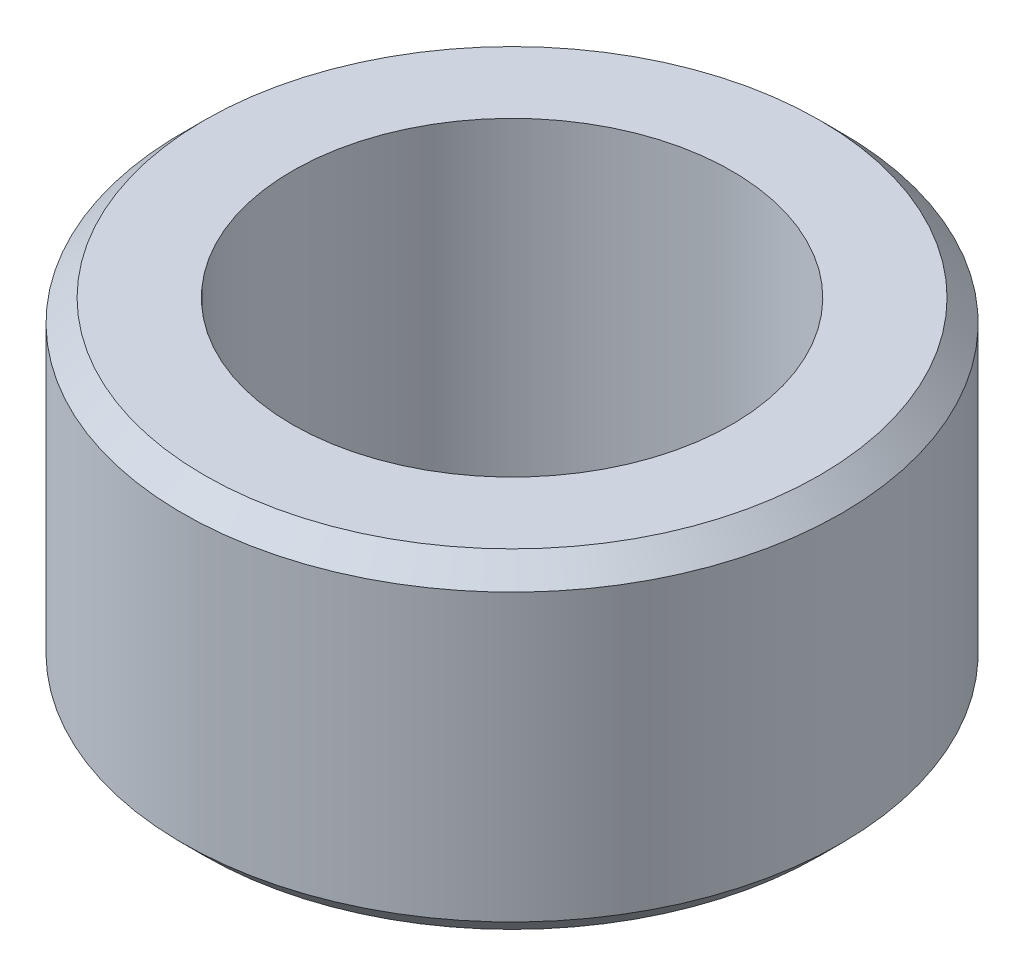
SolidWorks part; units mm, degrees
ref_plane "前视基准面" through (0, 0, 0) normal (0, 0, 1) x (1, 0, 0)
ref_plane "上视基准面" through (0, 0, 0) normal (0, 1, 0) x (1, 0, 0)
ref_plane "右视基准面" through (0, 0, 0) normal (1, 0, 0) x (0, 0, -1)
other "Configuration Table"
sketch "草图1" plane through (0, 0, 0) normal (0, 1, 0) x (1, 0, 0)
  circle A0 centre (0, 0) radius 15
  circle A1 centre (0, 0) radius 10
  dimension "D1" = 30
  dimension "D2" = 20
extrude "凸台-拉伸1" add sketch "草图1" along normal blind 15
sketch "草图2" plane through (0, 0, 0) normal (0, 0, 1) x (1, 0, 0)
  line L0 (0, -1000) -> (0, 49000) construction
  line L1 (-15, 15) -> (-14, 15)
  line L2 (15, 15) -> (-15, 15) construction
  line L3 (-14, 15) -> (-15, 14)
  line L4 (-15, 14) -> (-15, 15)
  line L5 (-15, 0) -> (-14, 0)
  line L6 (-15, 0) -> (15, 0) construction
  line L7 (-14, 0) -> (-15, 1)
  line L8 (-15, 1) -> (-15, 0)
  dimension "D1" = 1
  dimension "D2" = 1
  dimension "D3" = 1
  dimension "D4" = 1
revolve "切除-旋转1" cut sketch "草图2" angle 360 about L0
